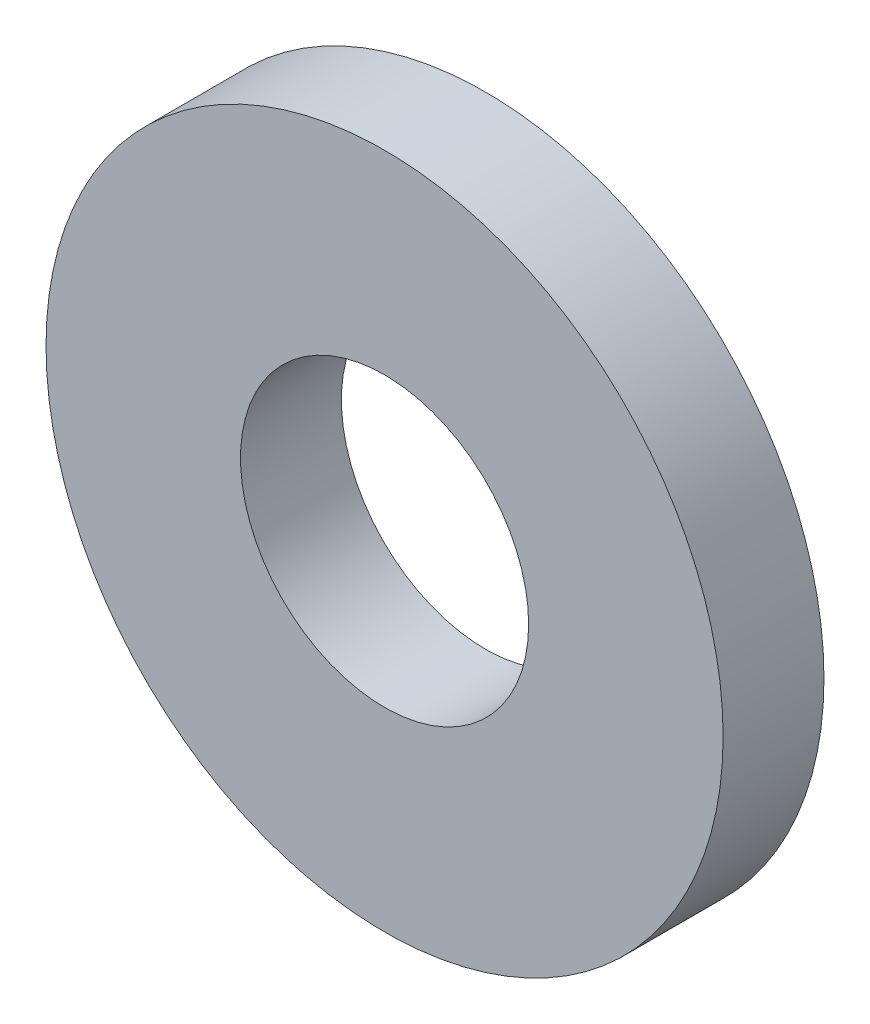
SolidWorks part; units mm, degrees
material "BUTYL"
ref_plane "Front Plane" through (0, 0, 0) normal (0, 0, 1) x (1, 0, 0)
ref_plane "Top Plane" through (0, 0, 0) normal (0, 1, 0) x (1, 0, 0)
ref_plane "Right Plane" through (0, 0, 0) normal (1, 0, 0) x (0, 0, -1)
sketch "Sketch1" plane through (0, 0, 0) normal (0, 1, 0) x (1, 0, 0)
  line L0 (0, 0) -> (0, 79.029) construction
  line L1 (10, 3.5) -> (23.5, 3.5)
  line L2 (10, 3.5) -> (10, -3.5)
  line L3 (10, -3.5) -> (23.5, -3.5)
  line L4 (23.5, 3.5) -> (23.5, -3.5)
  line L5 (10, 3.5) -> (23.5, -3.5) construction
  line L6 (10, -3.5) -> (23.5, 3.5) construction
  point P0 (16.75, 0)
  dimension "D1" = 10
  dimension "D2" = 23.5
  dimension "D3" = 7
revolve "Revolve1" add sketch "Sketch1" angle 360 about L0
